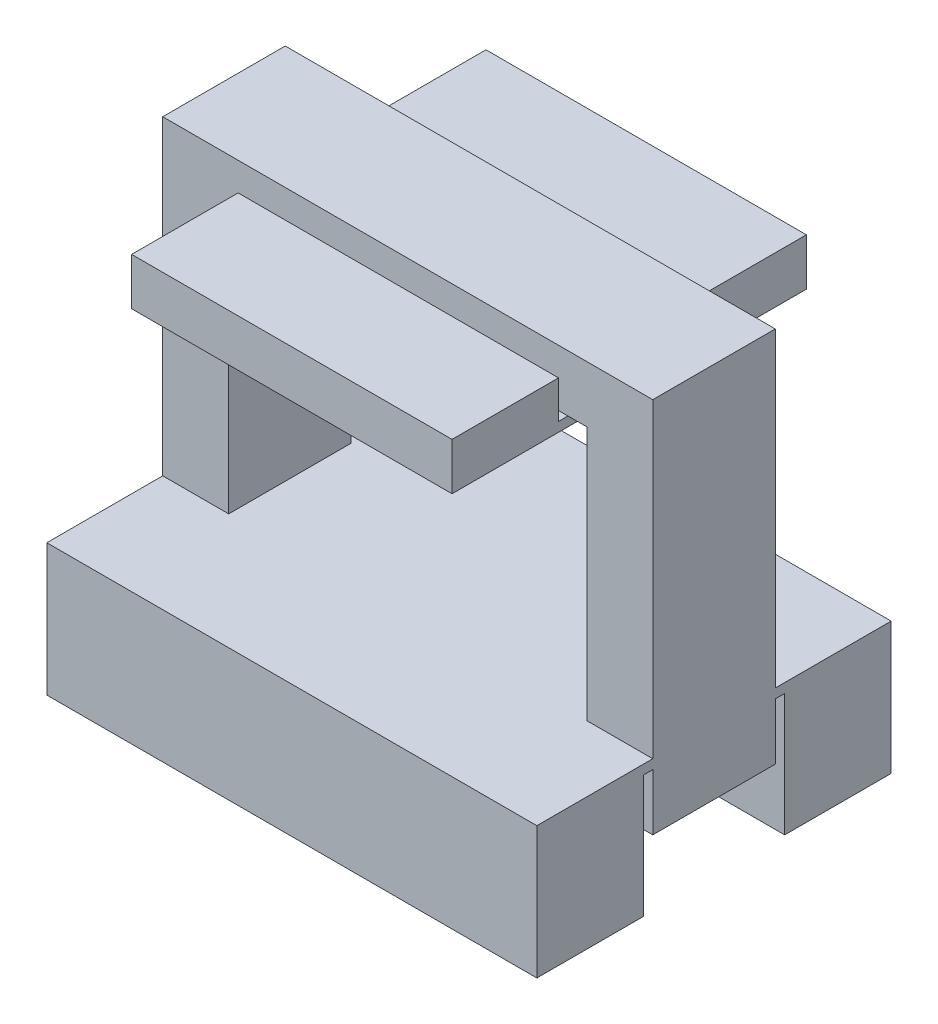
SolidWorks part; units mm, degrees
ref_plane "Спереди" through (0, 0, 0) normal (0, 0, 1) x (1, 0, 0)
ref_plane "Сверху" through (0, 0, 0) normal (0, 1, 0) x (1, 0, 0)
ref_plane "Справа" through (0, 0, 0) normal (1, 0, 0) x (0, 0, -1)
sketch "Эскиз2" plane through (0, 0, 0) normal (0, 1, 0) x (1, 0, 0)
  line L1 (-13, -3.25) -> (13, -3.25)
  line L2 (-13, -3.25) -> (-13, 3.25)
  line L3 (-13, 3.25) -> (13, 3.25)
  line L4 (13, -3.25) -> (13, 3.25)
  line L5 (-13, -3.25) -> (13, 3.25) construction
  line L6 (-13, 3.25) -> (13, -3.25) construction
  point P0 (0, 0)
  dimension "D1" = 26
  dimension "D2" = 6.5
extrude "Вытянуть1" add sketch "Эскиз2" along normal blind 20
sketch "Эскиз3" plane through (0, 0, 3.25) normal (0, 0, 1) x (1, 0, 0)
  line L0 (-13, 20) -> (-13, 0) construction
  line L1 (9.5, 17) -> (-9.5, 17)
  line L2 (9.5, 17) -> (9.5, 3)
  line L3 (9.5, 3) -> (-9.5, 3)
  line L4 (-9.5, 17) -> (-9.5, 3)
  line L5 (-13, 20) -> (13, 20) construction
  line L6 (-13, 0) -> (13, 0) construction
  line L7 (13, 20) -> (13, 0) construction
  dimension "D1" = 3.5
  dimension "D2" = 3
  dimension "D3" = 3
  dimension "D4" = 3.5
extrude "Вытянуть2" cut sketch "Эскиз3" against normal through all
sketch "Эскиз4" plane through (0, 17, 0) normal (0, -1, 0) x (1, 0, 0)
  line L1 (-8.5, -9.4) -> (8.5, -9.4)
  line L2 (-8.5, -9.4) -> (-8.5, 9.4)
  line L3 (-8.5, 9.4) -> (8.5, 9.4)
  line L4 (8.5, -9.4) -> (8.5, 9.4)
  line L5 (-8.5, -9.4) -> (8.5, 9.4) construction
  line L6 (-8.5, 9.4) -> (8.5, -9.4) construction
  point P0 (0, 0)
  dimension "D1" = 17
  dimension "D2" = 18.8
extrude "Вытянуть3" add sketch "Эскиз4" along normal blind 0.5 and the other way blind 2
sketch "Эскиз5" plane through (8.5, 0, 0) normal (1, 0, 0) x (0, 0, -1)
  line L0 (-3.25, 17) -> (-3.25, 19)
  line L1 (-3.25, 17) -> (-3.75, 17)
  line L2 (-3.25, 19) -> (-3.75, 19)
  line L3 (-3.75, 17) -> (-3.75, 19)
  line L4 (3.25, 17) -> (3.25, 19)
  line L5 (3.25, 17) -> (3.75, 17)
  line L6 (3.25, 19) -> (3.75, 19)
  line L7 (3.75, 17) -> (3.75, 19)
  dimension "D1" = 0.5
  dimension "D2" = 0.5
extrude "Вытянуть4" cut sketch "Эскиз5" against normal through all
sketch "Эскиз6" plane through (0, 3, 0) normal (0, 1, 0) x (-1, 0, 0)
  line L1 (13, -9.4) -> (-13, -9.4)
  line L2 (13, -9.4) -> (13, 9.4)
  line L3 (13, 9.4) -> (-13, 9.4)
  line L4 (-13, -9.4) -> (-13, 9.4)
  line L5 (13, -9.4) -> (-13, 9.4) construction
  line L6 (13, 9.4) -> (-13, -9.4) construction
  point P0 (0, 0)
  dimension "D1" = 26
  dimension "D2" = 18.8
sketch "Эскиз9" plane through (13, 0, 0) normal (1, 0, 0) x (0, 0, -1)
  line L0 (-3.25, 0) -> (-3.25, 3)
  line L1 (-3.25, 20) -> (-3.25, 0) construction
  line L2 (-3.25, 3) -> (-3.75, 3)
  line L3 (-3.75, 3) -> (-3.75, -3.5)
  line L4 (0, 0) -> (0, 2.0622) construction
  line L5 (-3.25, 0) -> (3.25, 0) construction
  line L6 (3.25, 0) -> (3.25, 3)
  line L7 (3.25, 3) -> (3.75, 3)
  line L8 (3.75, 3) -> (3.75, -3.5)
  line L9 (-3.25, 0) -> (3.25, 0)
  line L10 (3.75, -3.5) -> (-3.75, -3.5)
  dimension "D1" = 3
  dimension "D2" = 0.5
  dimension "D3" = 6.5
extrude "Вытянуть7" add sketch "Эскиз6" along normal blind 0.5 and the other way blind 6.5
extrude "Вытянуть8" cut sketch "Эскиз9" against normal through all
